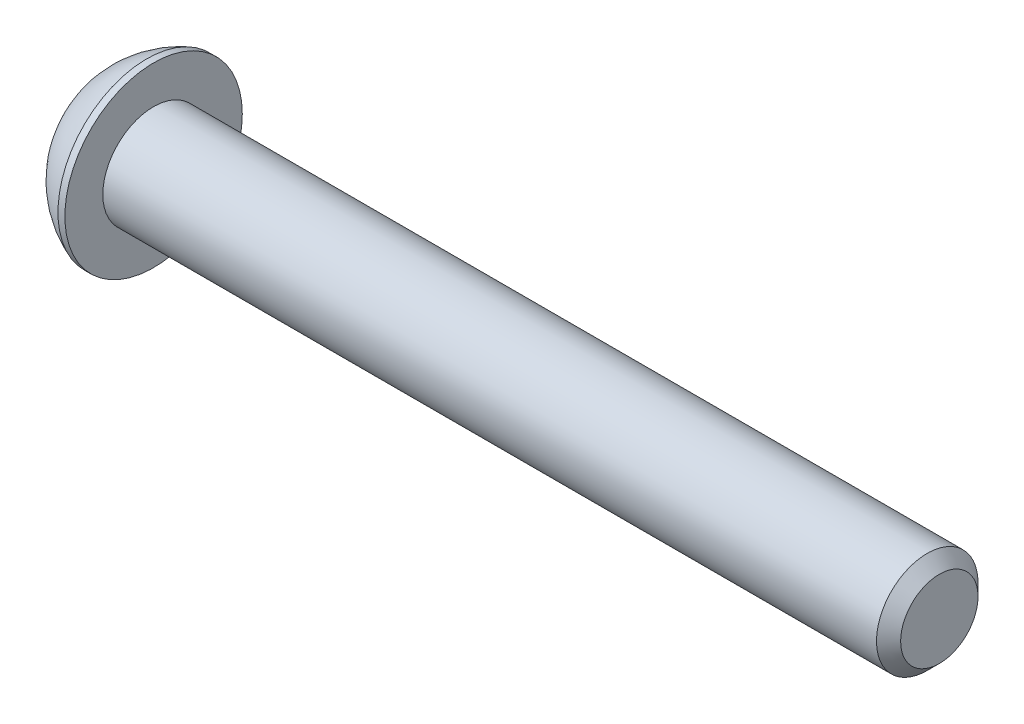
SolidWorks part; units mm, degrees
ref_plane "Front Plane" through (0, 0, 0) normal (0, 0, 1) x (1, 0, 0)
ref_plane "Top Plane" through (0, 0, 0) normal (0, 1, 0) x (1, 0, 0)
ref_plane "Right Plane" through (0, 0, 0) normal (1, 0, 0) x (0, 0, -1)
sketch "Sketch1" plane through (0, 0, 0) normal (0, 0, 1) x (1, 0, 0)
  line L0 (-3.3528, 3.175) -> (-3.3528, 0)
  line L1 (-3.3528, 0) -> (0, 0)
  line L2 (0, 0) -> (0, 5.5499)
  line L3 (0, 5.5499) -> (-0.4318, 5.5499)
  line L4 (-3.3528, 0) -> (0, 0) construction
  arc A0 (-0.4318, 5.5499) -> (-3.3528, 3.175) centre (1.6473, 0.0089) ccw
revolve "Revolve1" add sketch "Sketch1" angle 360 about L4
sketch "Sketch2" plane through (0, 0, 0) normal (1, 0, 0) x (0, 0, -1)
  circle A0 centre (0, 0) radius 3.175
extrude "Boss-Extrude1" add sketch "Sketch2" along normal blind 49.149
sketch "Sketch3" plane through (-3.3528, 0, 0) normal (-1, 0, 0) x (0, 0, 1)
  line L0 (2.2914, 0) -> (1.1457, 1.9844)
  line L1 (1.1457, 1.9844) -> (-1.1457, 1.9844)
  line L2 (-1.1457, 1.9844) -> (-2.2914, 0)
  line L3 (-2.2914, 0) -> (-1.1457, -1.9844)
  line L4 (-1.1457, -1.9844) -> (1.1457, -1.9844)
  line L5 (1.1457, -1.9844) -> (2.2914, 0)
extrude "Cut-Extrude1" cut sketch "Sketch3" against normal blind 2.2225
chamfer "Chamfer1" distance 0.7557 angle 45 1 edges at (49.149, 0, -3.175)
